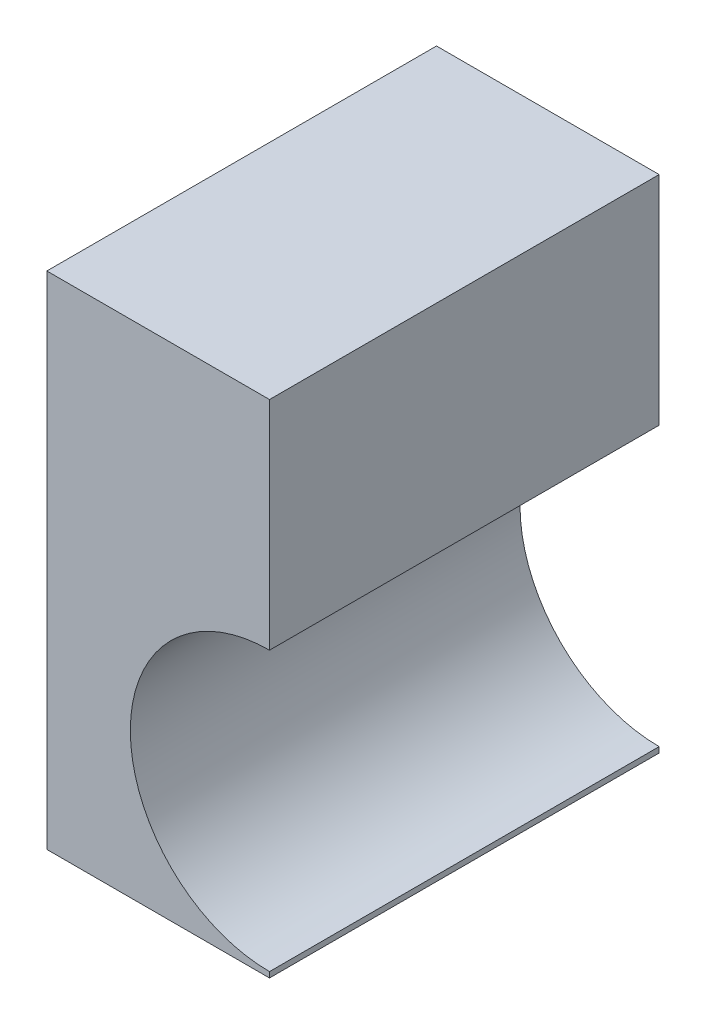
SolidWorks part; units mm, degrees
ref_plane "Front Plane" through (0, 0, 0) normal (0, 0, 1) x (1, 0, 0)
ref_plane "Top Plane" through (0, 0, 0) normal (0, 1, 0) x (1, 0, 0)
ref_plane "Right Plane" through (0, 0, 0) normal (1, 0, 0) x (0, 0, -1)
sketch "Sketch1" plane through (0, 0, 0) normal (0, 0, 1) x (1, 0, 0)
  line L0 (0, 0) -> (0, 0.5)
  line L1 (0, 25.5) -> (0, 45)
  line L2 (0, 45) -> (-20, 45)
  line L3 (-20, 45) -> (-20, 0)
  line L4 (-20, 0) -> (0, 0)
  arc A0 (0, 0.5) -> (0, 25.5) centre (0, 13) cw
  dimension "D1" = 12.5
  dimension "D2" = 45
  dimension "D3" = 20
  dimension "D4" = 0.5
extrude "Boss-Extrude1" add sketch "Sketch1" along normal blind 35
